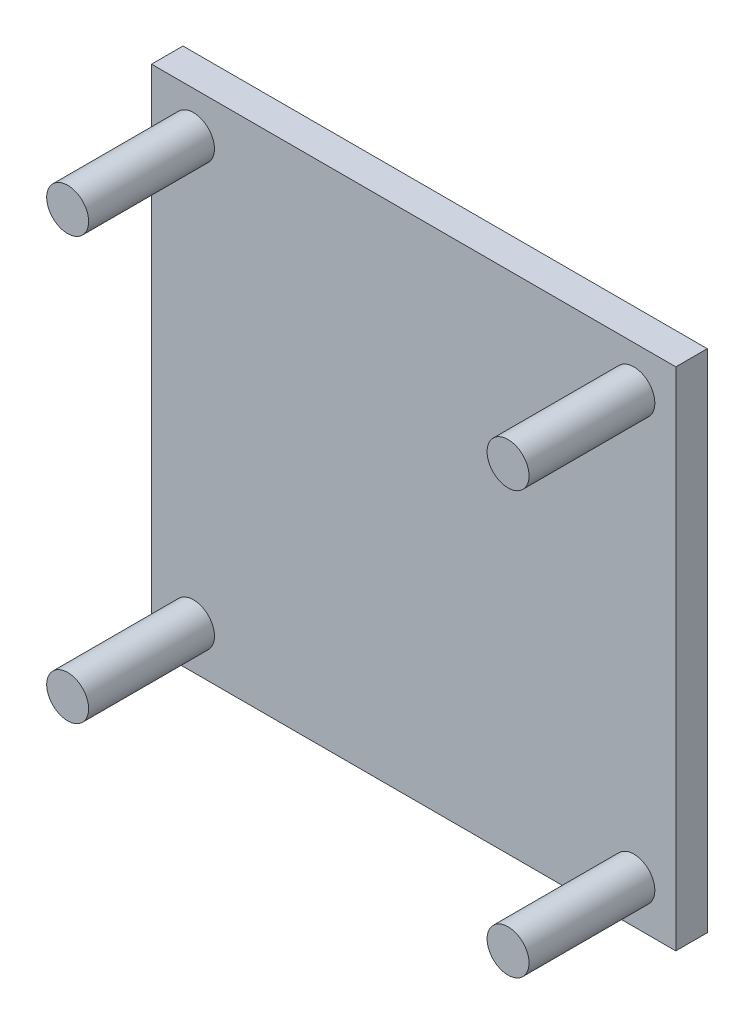
SolidWorks part; units mm, degrees
ref_plane "Спереди" through (0, 0, 0) normal (0, 0, 1) x (1, 0, 0)
ref_plane "Сверху" through (0, 0, 0) normal (0, 1, 0) x (1, 0, 0)
ref_plane "Справа" through (0, 0, 0) normal (1, 0, 0) x (0, 0, -1)
sketch "Эскиз1" plane through (0, 0, 0) normal (0, 0, 1) x (1, 0, 0)
  line L0 (-25, -24.1209) -> (25, -24.1209)
  line L1 (25, -24.1209) -> (25, 24.1209)
  line L2 (25, 24.1209) -> (-25, 24.1209)
  line L3 (-25, 24.1209) -> (-25, -24.1209)
extrude "Former_base" add sketch "Эскиз1" along normal blind 3
sketch "Эскиз2" plane through (0, 0, 0) normal (0, 0, 1) x (1, 0, 0)
  circle A0 centre (-21, -20.1209) radius 2
  circle A1 centre (-21, 20.1209) radius 2
  circle A2 centre (21, -20.1209) radius 2
  circle A3 centre (21, 20.1209) radius 2
extrude "Former_posts" add sketch "Эскиз2" along normal blind 12 from offset 3
